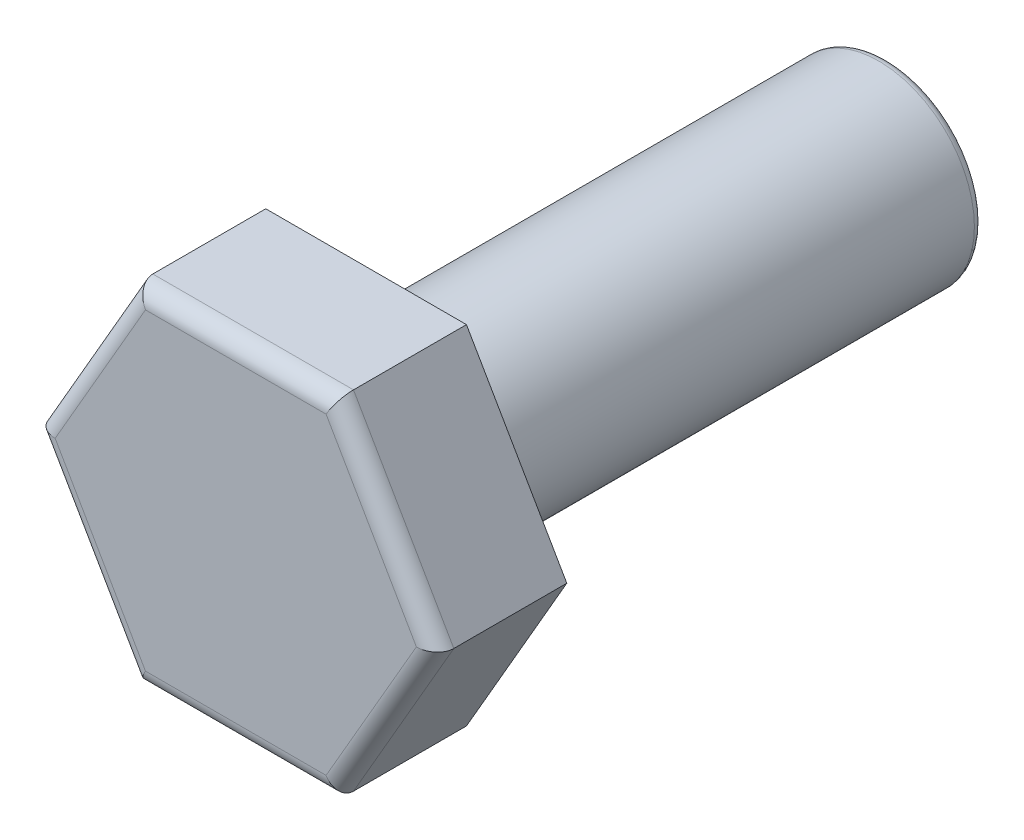
SolidWorks part; units mm, degrees
ref_plane "前视基准面" through (0, 0, 0) normal (0, 0, 1) x (1, 0, 0)
ref_plane "上视基准面" through (0, 0, 0) normal (0, 1, 0) x (1, 0, 0)
ref_plane "右视基准面" through (0, 0, 0) normal (1, 0, 0) x (0, 0, -1)
sketch "草图1" plane through (0, 0, 0) normal (0, 0, 1) x (1, 0, 0)
  circle A0 centre (0, 0) radius 11
  dimension "D1" = 22
extrude "凸台-拉伸1" add sketch "草图1" along normal blind 75
sketch "草图3" plane through (0, 0, 75) normal (0, 0, 1) x (1, 0, 0)
  line L1 (11.547, -20) -> (23.094, 0)
  line L2 (23.094, 0) -> (11.547, 20)
  line L3 (11.547, 20) -> (-11.547, 20)
  line L4 (-11.547, 20) -> (-23.094, 0)
  line L5 (-23.094, 0) -> (-11.547, -20)
  line L6 (-11.547, -20) -> (11.547, -20)
  circle A0 centre (0, 0) radius 20 construction
  dimension "D1" = 40
extrude "凸台-拉伸2" add sketch "草图3" against normal blind 15
fillet "圆角1" radius 2 6 edges at (17.3205, -10, 75) (0, -20, 75) (-17.3205, -10, 75) (-17.3205, 10, 75) (0, 20, 75) (17.3205, 10, 75)
fillet "圆角2" radius 1 1 edges at (11, 0, 0)
